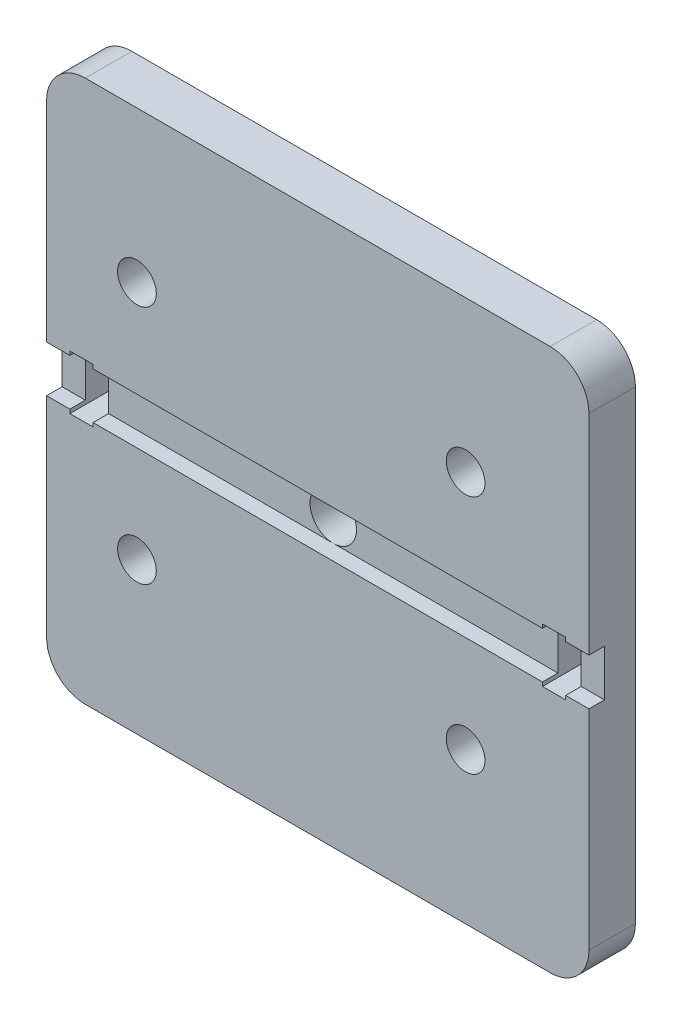
SolidWorks part; units mm, degrees
material "Oak"
ref_plane "Front Plane" through (0, 0, 0) normal (0, 0, 1) x (1, 0, 0)
ref_plane "Top Plane" through (0, 0, 0) normal (0, 1, 0) x (1, 0, 0)
ref_plane "Right Plane" through (0, 0, 0) normal (1, 0, 0) x (0, 0, -1)
sketch "Sketch1" plane through (0, 0, 0) normal (0, 0, 1) x (1, 0, 0)
  line L0 (-51.4706, 404.6176) -> (18.5294, 404.6176)
  line L1 (13.5294, 424.1176) -> (-46.4706, 424.1176)
  line L2 (18.5294, 419.1176) -> (18.5294, 359.1176)
  line L3 (13.5294, 354.1176) -> (-46.4706, 354.1176)
  line L4 (-51.4706, 419.1176) -> (-51.4706, 359.1176)
  line L5 (-51.4706, 373.6176) -> (18.5294, 373.6176)
  line L7 (-48.4706, 392.6176) -> (-45.4706, 392.6176)
  line L8 (-48.4706, 392.6176) -> (-48.4706, 385.6176)
  line L9 (-48.4706, 385.6176) -> (-45.4706, 385.6176)
  line L10 (-45.4706, 392.6176) -> (-45.4706, 385.6176)
  line L11 (15.5294, 392.6176) -> (12.5294, 392.6176)
  line L12 (15.5294, 392.6176) -> (15.5294, 385.6176)
  line L13 (15.5294, 385.6176) -> (12.5294, 385.6176)
  line L14 (12.5294, 392.6176) -> (12.5294, 385.6176)
  circle A0 centre (-39.8106, 404.6176) radius 2.5
  circle A1 centre (2.6121, 404.6176) radius 2.5
  circle A2 centre (-39.8106, 373.6176) radius 2.5
  circle A3 centre (2.6121, 373.6176) radius 2.5
  arc A4 (-46.4706, 354.1176) -> (-51.4706, 359.1176) centre (-46.4706, 359.1176) cw
  arc A5 (18.5294, 359.1176) -> (13.5294, 354.1176) centre (13.5294, 359.1176) cw
  arc A6 (13.5294, 424.1176) -> (18.5294, 419.1176) centre (13.5294, 419.1176) cw
  arc A7 (-46.4706, 424.1176) -> (-51.4706, 419.1176) centre (-46.4706, 419.1176) ccw
  point P28 (18.5294, 354.1176)
  point P31 (18.5294, 424.1176)
  point P34 (-51.4706, 424.1176)
  dimension "D5" = 5
  dimension "D6" = 5
  dimension "D7" = 5
  dimension "D8" = 5
  dimension "D18" = 5
  dimension "D1" = 70
  dimension "D2" = 70
  dimension "D3" = 19.5
  dimension "D4" = 19.5
  dimension "D9" = 3
  dimension "D10" = 3
  dimension "D11" = 7
  dimension "D12" = 7
  dimension "D13" = 31.5
  dimension "D14" = 31.5
  dimension "D15" = 31.5
  dimension "D16" = 3
  dimension "D17" = 3
extrude "Boss-Extrude1" add sketch "Sketch1" along normal blind 6 contours L1 A7 L4 L0 A0 A1 L2 A6 | A3 L5 L2 L0 A1 A0 L4 A2 L14 L11 L12 L13 L7 L10 L9 L8 | A5 L2 L5 A3 A2 L4 A4 L3
sketch "Sketch2" plane through (0, 0, 6) normal (0, 0, 1) x (1, 0, 0)
  line L0 (-51.4706, 389.1176) -> (18.5294, 389.1176)
  line L1 (-51.4706, 419.1176) -> (-51.4706, 359.1176) construction
  line L2 (18.5294, 419.1176) -> (18.5294, 359.1176) construction
  line L3 (-51.4706, 389.1176) -> (18.5294, 389.1176) construction
  line L4 (-51.4706, 392.1176) -> (18.5294, 392.1176)
  line L5 (-51.4706, 392.1176) -> (-51.4706, 386.1176)
  line L6 (-51.4706, 386.1176) -> (18.5294, 386.1176)
  line L7 (18.5294, 392.1176) -> (18.5294, 386.1176)
  line L9 (-51.4706, 392.1176) -> (18.5294, 392.1176)
  line L10 (-51.4706, 392.1176) -> (-51.4706, 386.1176)
  line L11 (-51.4706, 386.1176) -> (18.5294, 386.1176)
  line L12 (18.5294, 392.1176) -> (18.5294, 386.1176)
  point P10 (-16.4706, 389.1176)
  point P11 (-16.4706, 389.1176)
  dimension "D1" = 6
  dimension "D2" = 3
sketch "Sketch5" plane through (0, 0, 6) normal (0, 0, 1) x (1, 0, 0)
  line L0 (-51.4706, 389.1176) -> (18.5294, 389.1176) construction
  line L1 (-51.4706, 392.1176) -> (18.5294, 392.1176)
  line L2 (-51.4706, 392.1176) -> (-51.4706, 386.1176)
  line L3 (-51.4706, 386.1176) -> (18.5294, 386.1176)
  line L4 (18.5294, 392.1176) -> (18.5294, 386.1176)
  dimension "D1" = 6
  dimension "D2" = 70
  dimension "D3" = 3
extrude "Cut-Extrude2" cut sketch "Sketch5" against normal blind 2
sketch "Sketch6" plane through (0, 0, 4) normal (0, 0, 1) x (1, 0, 0)
  line L0 (-51.4706, 389.1176) -> (18.5294, 389.1176) construction
  circle A0 centre (-16.4706, 389.1176) radius 3
extrude "Cut-Extrude3" cut sketch "Sketch6" against normal blind 10
